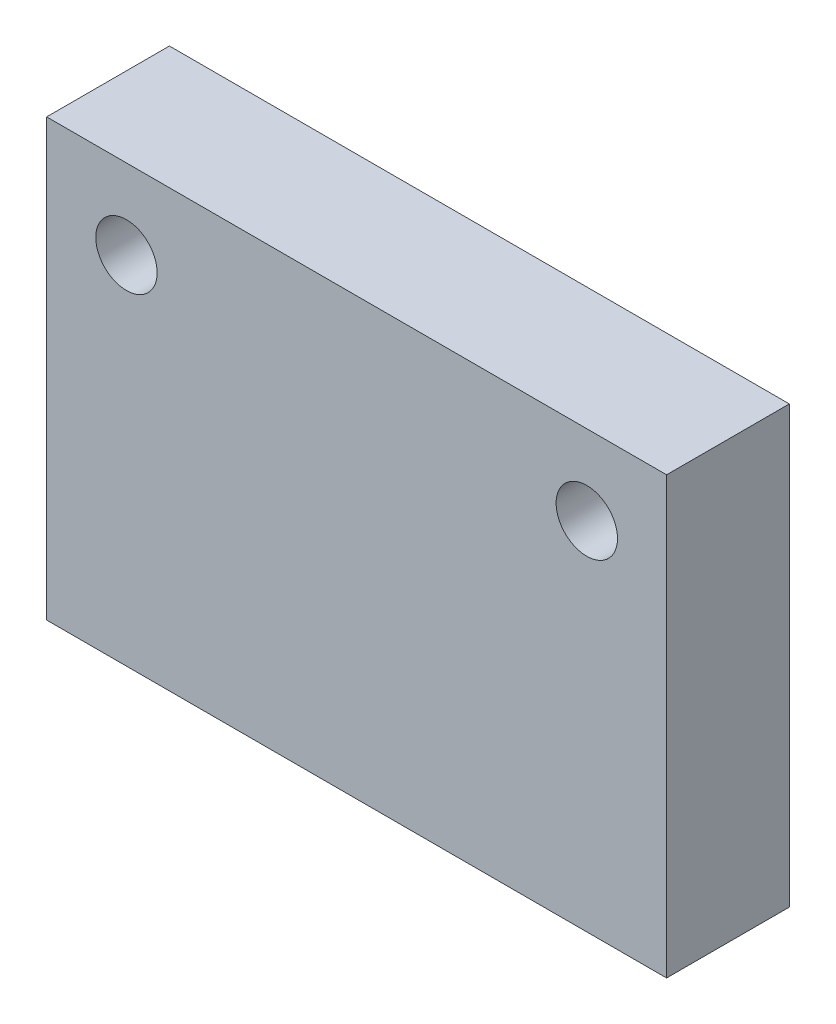
SolidWorks part; units mm, degrees
ref_plane "Front Plane" through (0, 0, 0) normal (0, 0, 1) x (1, 0, 0)
ref_plane "Top Plane" through (0, 0, 0) normal (0, 1, 0) x (1, 0, 0)
ref_plane "Right Plane" through (0, 0, 0) normal (1, 0, 0) x (0, 0, -1)
sketch "Sketch1" plane through (0, 0, 0) normal (0, 0, 1) x (1, 0, 0)
  line L0 (0, 10.15) -> (0, -10.05) construction
  line L1 (-10.1, 10.15) -> (10.1, 10.15)
  line L2 (-10.1, 10.15) -> (-10.1, -10.05)
  line L3 (-10.1, -10.05) -> (10.1, -10.05)
  line L4 (10.1, 10.15) -> (10.1, -10.05)
  line L5 (-10.1, 0.05) -> (10.1, 0.05) construction
  line L6 (7.5, 7.55) -> (7.5, -8.7) construction
  line L7 (0, 10.15) -> (7.5, 10.15) construction
  line L8 (7.5, 10.15) -> (7.5, 7.55) construction
  circle A11 centre (7.5, 7.55) radius 1
  circle A12 centre (-7.5, 7.55) radius 1
  circle A13 centre (7.5, -8.7) radius 1
  circle A14 centre (-7.5, -8.7) radius 1
  point P0 (0, 0)
  dimension "D1" = 20.2
  dimension "D3" = 7.5
  dimension "D5" = 2
  dimension "D6" = 16.25
  dimension "D7" = 2
  dimension "D2" = 20.2
  dimension "D4" = 2.6
extrude "Boss-Extrude1" add sketch "Sketch1" along normal blind 4
sketch "Sketch2" plane through (0, 0, 4) normal (0, 0, 1) x (1, 0, 0)
  line L0 (0, 4) -> (0, -20.32) construction
  circle A0 centre (0, -13.32) radius 7
  circle A2 centre (0, 0) radius 4
  dimension "D1" = 14
  dimension "D3" = 8
  dimension "D2" = 24.32
extrude "Cut-Extrude1" cut sketch "Sketch2" against normal blind 4
sketch "Sketch3" plane through (0, 0, 4) normal (0, 0, 1) x (1, 0, 0)
  circle A0 centre (0, 0) radius 4
  dimension "D1" = 8
extrude "Boss-Extrude2" add sketch "Sketch3" against normal blind 4
ref_plane "Plane1" through (0, 0, 4) normal (0, 0, 1) x (1, 0, 0)
sketch "Sketch4" plane through (0, 0, 4) normal (0, 0, 1) x (1, 0, 0)
  line L0 (-10.1, -10.05) -> (-10.1, -4.05) construction
  line L1 (-10.1, -10.05) -> (10.1, -10.05)
  line L2 (-10.1, 10.15) -> (-10.1, -10.05) construction
  line L3 (-10.1, -10.05) -> (-10.1, -4.05)
  line L4 (10.1, -10.05) -> (10.1, 10.15) construction
  line L9 (-10.1, -4.05) -> (10.1, -4.05)
  line L10 (10.1, -4.05) -> (10.1, -10.05)
  dimension "D1" = 6
extrude "Cut-Extrude2" cut sketch "Sketch4" against normal blind 10
